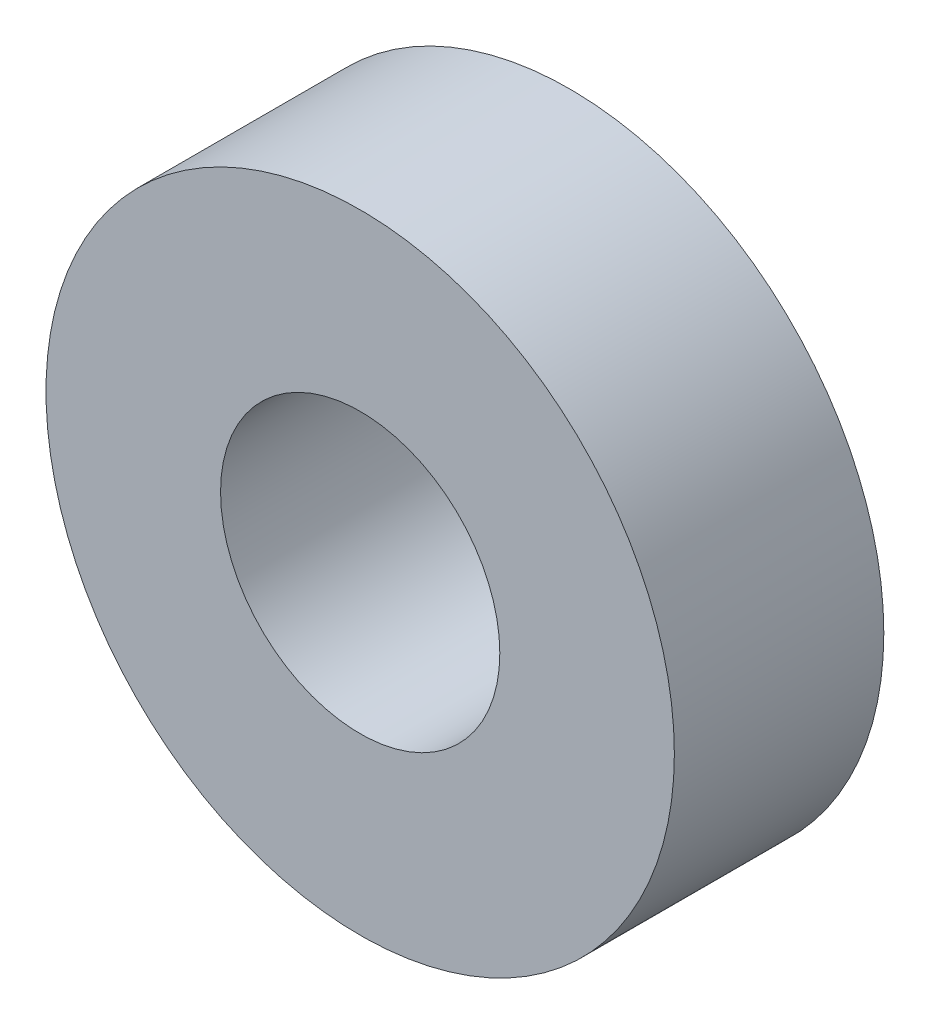
SolidWorks part; units mm, degrees
ref_plane "前基準面" through (0, 0, 0) normal (0, 0, 1) x (1, 0, 0)
ref_plane "上基準面" through (0, 0, 0) normal (0, 1, 0) x (1, 0, 0)
ref_plane "右基準面" through (0, 0, 0) normal (1, 0, 0) x (0, 0, -1)
sketch "草圖1" plane through (0, 0, 0) normal (0, 0, 1) x (1, 0, 0)
  circle A0 centre (0, 0) radius 2
  circle A1 centre (0, 0) radius 4.5
  dimension "D1" = 4
  dimension "D2" = 9
extrude "填料-伸長1" add sketch "草圖1" along normal blind 3
ref_plane "平面1" through (0, 0, -7.25) normal (0, 0, 1) x (1, 0, 0)
sketch "草圖2" plane through (0, 0, -7.25) normal (0, 0, 1) x (1, 0, 0)
  line L0 (69.95, 0.5) -> (55.63, 0.5)
  circle A0 centre (69.95, 0.5) radius 1.5
  dimension "D1" = 0.5
  dimension "D2" = 69.95
  dimension "D3" = 3
  dimension "D4" = 14.32
